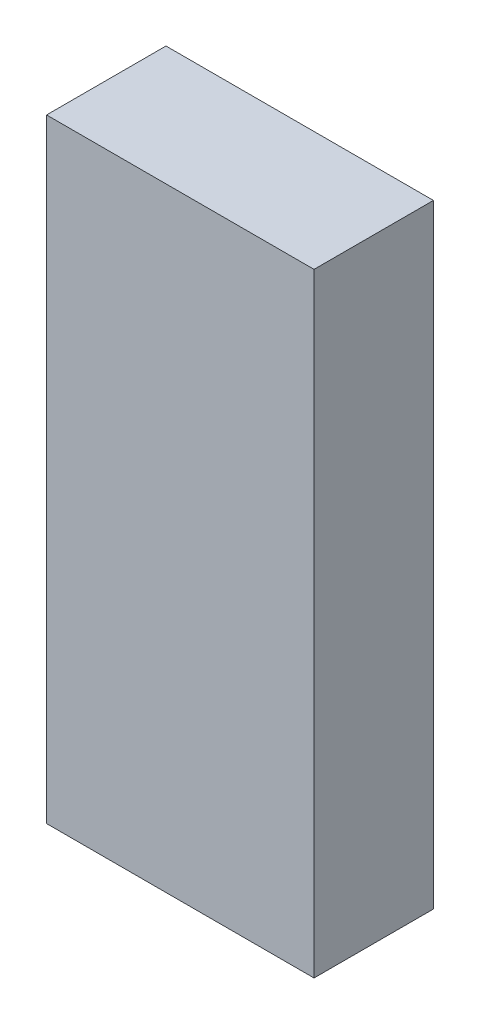
SolidWorks part; units mm, degrees
ref_plane "Front Plane" through (0, 0, 0) normal (0, 0, 1) x (1, 0, 0)
ref_plane "Top Plane" through (0, 0, 0) normal (0, 1, 0) x (1, 0, 0)
ref_plane "Right Plane" through (0, 0, 0) normal (1, 0, 0) x (0, 0, -1)
sketch "Sketch1" plane through (0, 0, 0) normal (0, 1, 0) x (1, 0, 0)
  line L1 (28, -12.5) -> (-28, -12.5)
  line L2 (28, -12.5) -> (28, 12.5)
  line L3 (28, 12.5) -> (-28, 12.5)
  line L4 (-28, -12.5) -> (-28, 12.5)
  line L5 (28, -12.5) -> (-28, 12.5) construction
  line L6 (28, 12.5) -> (-28, -12.5) construction
  point P0 (0, 0)
  dimension "D1" = 56
  dimension "D2" = 25
extrude "Boss-Extrude1" add sketch "Sketch1" along normal blind 128.5
